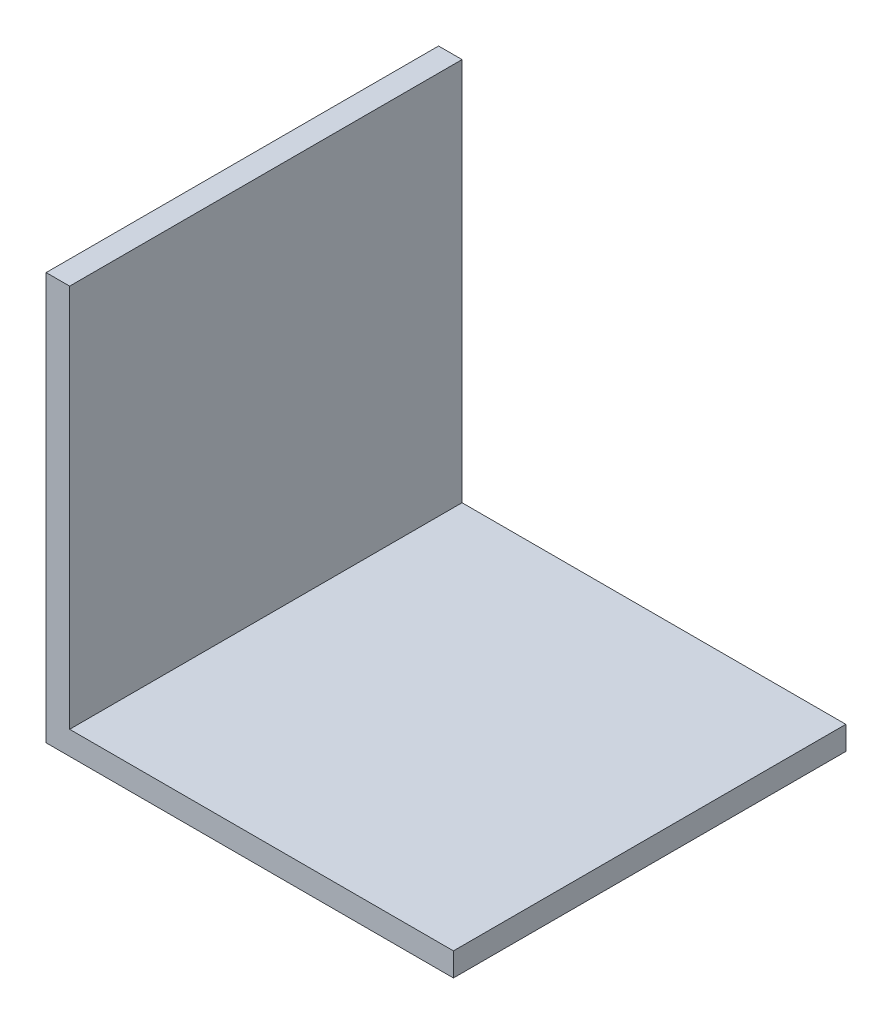
SolidWorks part; units mm, degrees
ref_plane "Front Plane" through (0, 0, 0) normal (0, 0, 1) x (1, 0, 0)
ref_plane "Top Plane" through (0, 0, 0) normal (0, 1, 0) x (1, 0, 0)
ref_plane "Right Plane" through (0, 0, 0) normal (1, 0, 0) x (0, 0, -1)
sketch "Sketch1" plane through (0, 0, 0) normal (0, 0, 1) x (1, 0, 0)
  line L0 (0, 0) -> (0, 52)
  line L1 (0, 0) -> (52, 0)
  line L2 (0, 52) -> (3, 52)
  line L3 (3, 52) -> (3, 3)
  line L4 (3, 3) -> (52, 3)
  line L5 (52, 3) -> (52, 0)
  dimension "D1" = 52
  dimension "D2" = 52
  dimension "D3" = 3
  dimension "D4" = 3
extrude "Boss-Extrude1" add sketch "Sketch1" along normal mid plane 50.1
